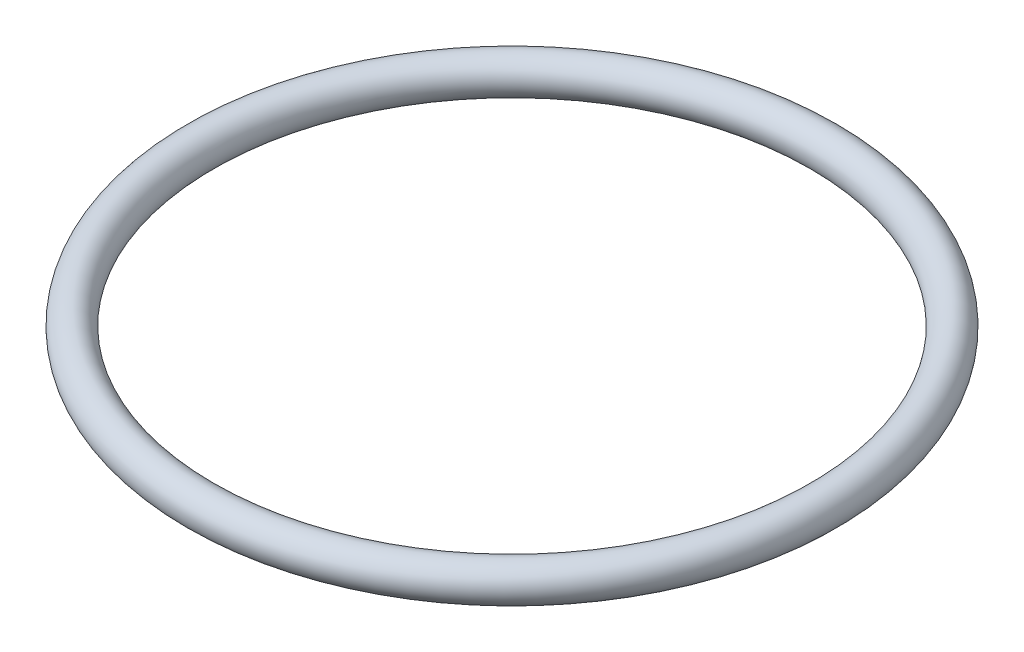
SolidWorks part; units mm, degrees
ref_plane "Спереди" through (0, 0, 0) normal (0, 0, 1) x (1, 0, 0)
ref_plane "Сверху" through (0, 0, 0) normal (0, 1, 0) x (1, 0, 0)
ref_plane "Справа" through (0, 0, 0) normal (1, 0, 0) x (0, 0, -1)
sketch "Эскиз1" plane through (0, 0, 0) normal (0, 0, 1) x (1, 0, 0)
  line L0 (0, 0) -> (-6.2627, 0) construction
  line L1 (0, 0) -> (0, 5.191) construction
  circle A0 centre (-21.25, 0) radius 1.25
  dimension "D1" = 2.5
  dimension "D2" = 42.5
revolve "Повернуть1" add sketch "Эскиз1" angle 360 about L1
